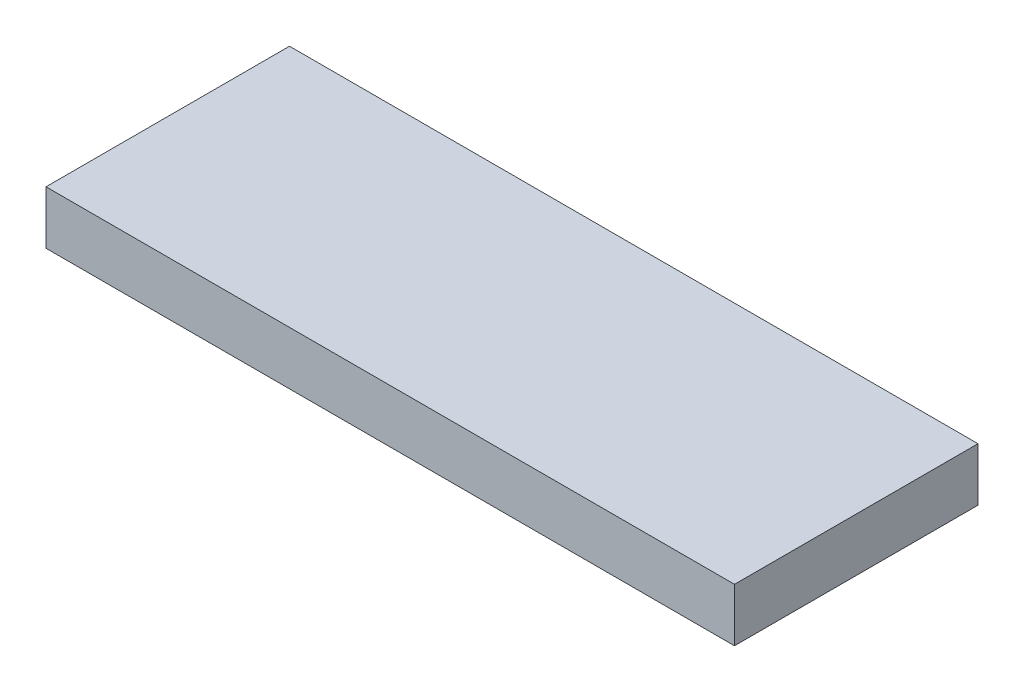
SolidWorks part; units mm, degrees
ref_plane "Front Plane" through (0, 0, 0) normal (0, 0, 1) x (1, 0, 0)
ref_plane "Top Plane" through (0, 0, 0) normal (0, 1, 0) x (1, 0, 0)
ref_plane "Right Plane" through (0, 0, 0) normal (1, 0, 0) x (0, 0, -1)
sketch "Sketch1" plane through (0, 0, 0) normal (0, 1, 0) x (1, 0, 0)
  line L1 (0, 0) -> (574.548, 0)
  line L2 (0, 0) -> (0, 203.2)
  line L3 (0, 203.2) -> (574.548, 203.2)
  line L4 (574.548, 0) -> (574.548, 203.2)
  dimension "D1" = 203.2
  dimension "D2" = 574.548
extrude "Boss-Extrude1" add sketch "Sketch1" along normal blind 44.45
